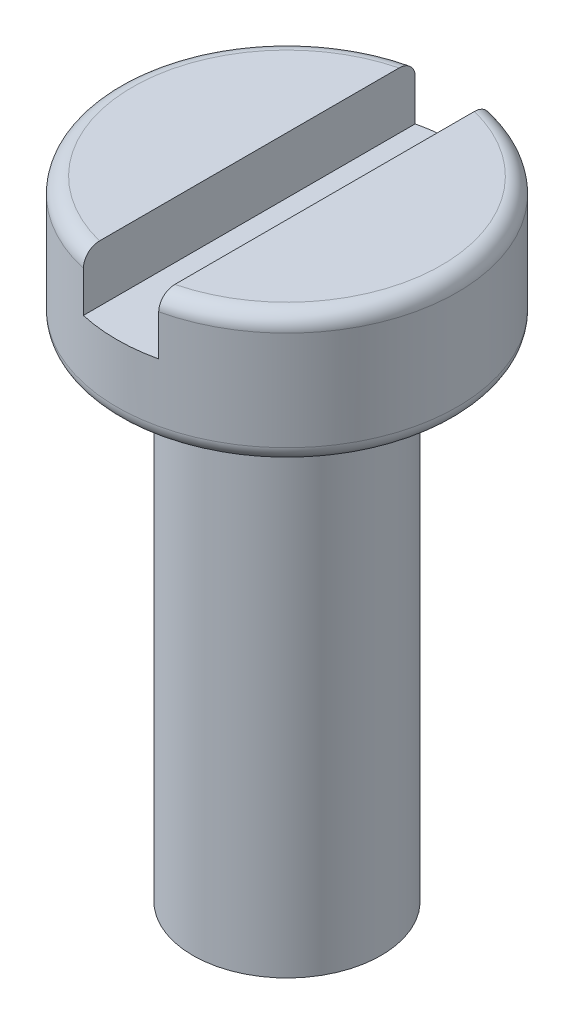
SolidWorks part; units mm, degrees
material "Plain Carbon Steel"
ref_plane "Front Plane" through (0, 0, 0) normal (0, 0, 1) x (1, 0, 0)
ref_plane "Top Plane" through (0, 0, 0) normal (0, 1, 0) x (1, 0, 0)
ref_plane "Right Plane" through (0, 0, 0) normal (1, 0, 0) x (0, 0, -1)
sketch "Sketch1" plane through (0, 0, 0) normal (0, 1, 0) x (1, 0, 0)
  circle A0 centre (0, 0) radius 2.71
  dimension "D1" = 5.42
extrude "Boss-Extrude1" add sketch "Sketch1" along normal blind 10
sketch "Sketch2" plane through (0, 10, 0) normal (0, 1, 0) x (1, 0, 0)
  circle A0 centre (0, 0) radius 1.5
  dimension "D1" = 3
extrude "Cut-Extrude1" cut sketch "Sketch2" against normal blind 7.92 flip side to cut
cosmetic thread "Cosmetic Thread1" parameters "D2"=2.439
fillet "Fillet1" radius 0.25 2 edges at (0, 0, 2.71) (0, 2.08, 2.71)
fillet "Fillet2" radius 0.15 1 edges at (0, 2.08, 1.5)
sketch "Sketch3" plane through (0, 0, 0) normal (0, -1, 0) x (1, 0, 0)
  line L0 (0, 2.71) -> (0, -2.71) construction
  line L1 (-0.6, -2.711) -> (-0.6, 2.711)
  line L2 (-0.6, -2.711) -> (0.6, -2.711)
  line L3 (-0.6, 2.711) -> (0.6, 2.711)
  line L4 (0.6, -2.711) -> (0.6, 2.711)
  line L5 (-0.6, -2.711) -> (0.6, 2.711) construction
  line L6 (-0.6, 2.711) -> (0.6, -2.711) construction
  circle A0 centre (0, 0) radius 2.71 construction
  point P6 (0, 0)
  dimension "D1" = 0.6
extrude "Cut-Extrude2" cut sketch "Sketch3" against normal blind 0.9
move or copy body "Body-Move/Copy1" bodies to move or copy 103 copy no rotation origin (0, 10, 0) rotation axis (1, 0, 0) rotation angle 180
